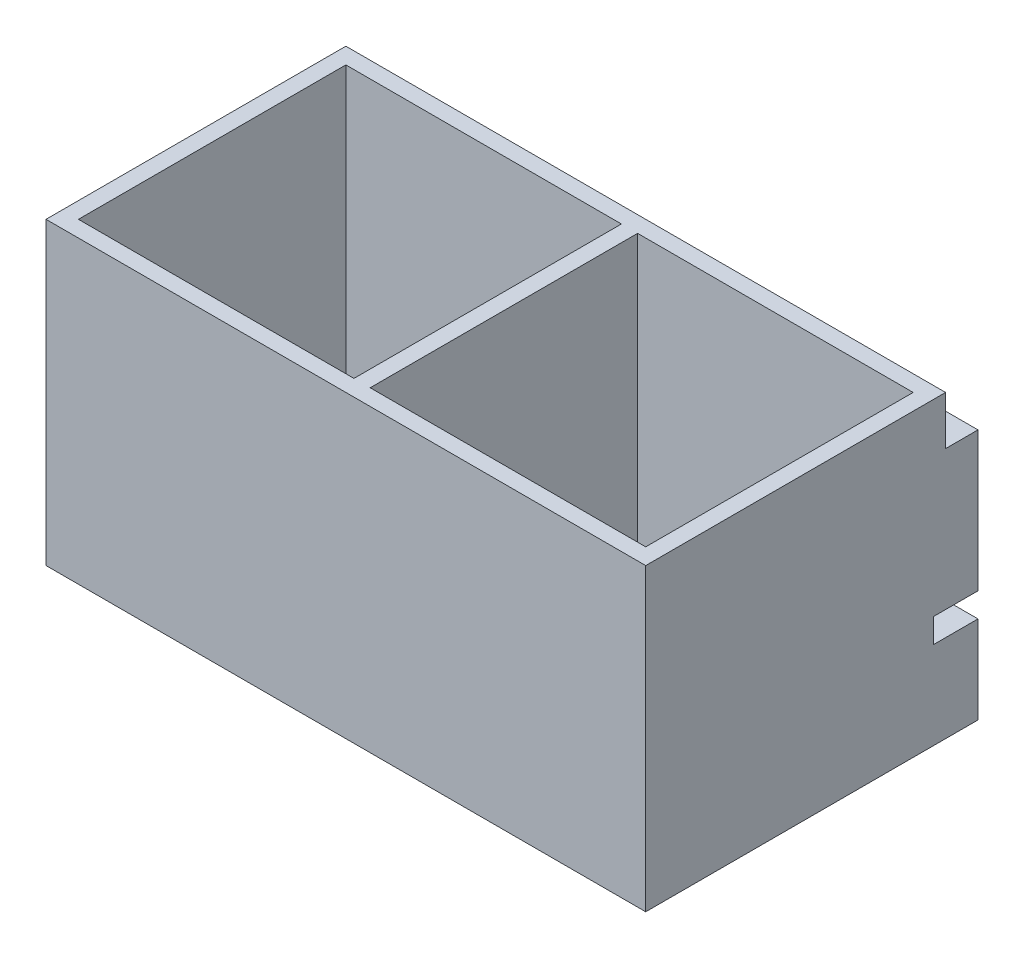
SolidWorks part; units mm, degrees
ref_plane "Front Plane" through (0, 0, 0) normal (0, 0, 1) x (1, 0, 0)
ref_plane "Top Plane" through (0, 0, 0) normal (0, 1, 0) x (1, 0, 0)
ref_plane "Right Plane" through (0, 0, 0) normal (1, 0, 0) x (0, 0, -1)
sketch "Sketch1" plane through (0, 0, 0) normal (0, 1, 0) x (1, 0, 0)
  line L1 (-70.6, 1.0159) -> (3.4, 1.0159)
  line L2 (-70.6, 1.0159) -> (-70.6, -35.9841)
  line L3 (-70.6, -35.9841) -> (3.4, -35.9841)
  line L4 (3.4, 1.0159) -> (3.4, -35.9841)
  dimension "D1" = 74
  dimension "D2" = 37
extrude "Boss-Extrude1" add sketch "Sketch1" along normal blind 37
sketch "Sketch3" plane through (0, 37, 0) normal (0, 1, 0) x (1, 0, 0)
  line L0 (-70.6, 1.0159) -> (-70.6, -35.9841) construction
  line L1 (-68.6, -0.9841) -> (-34.6, -0.9841)
  line L2 (-68.6, -0.9841) -> (-68.6, -33.9841)
  line L3 (-68.6, -33.9841) -> (-34.6, -33.9841)
  line L4 (-34.6, -0.9841) -> (-34.6, -33.9841)
  line L5 (-32.6, -0.9841) -> (1.4, -0.9841)
  line L6 (-32.6, -0.9841) -> (-32.6, -33.9841)
  line L7 (-32.6, -33.9841) -> (1.4, -33.9841)
  line L8 (1.4, -0.9841) -> (1.4, -33.9841)
  line L9 (3.4, 1.0159) -> (-70.6, 1.0159) construction
  line L10 (-70.6, -35.9841) -> (3.4, -35.9841) construction
  line L11 (3.4, -35.9841) -> (3.4, 1.0159) construction
  dimension "D1" = 2
  dimension "D2" = 2
  dimension "D3" = 2
  dimension "D4" = 2
  dimension "D5" = 2
  dimension "D6" = 2
  dimension "D7" = 34
  dimension "D8" = 34
extrude "Cut-Extrude1" cut sketch "Sketch3" against normal blind 35
sketch "Sketch5" plane through (0, 2, 0) normal (0, 1, 0) x (1, 0, 0)
  line L0 (-70.6, -35.9841) -> (3.4, -35.9841) construction
  line L1 (3.4, -35.9841) -> (3.4, 1.0159) construction
  line L2 (-70.6, 1.0159) -> (-70.6, -35.9841) construction
  circle A0 centre (-15.1, -17.4841) radius 13
  circle A1 centre (-52.1, -17.4841) radius 13
  dimension "D1" = 26
  dimension "D2" = 26
  dimension "D3" = 18.5
  dimension "D4" = 18.5
  dimension "D5" = 18.5
  dimension "D6" = 18.5
extrude "Cut-Extrude2" cut sketch "Sketch5" against normal blind 3.5
sketch "Sketch6" plane through (0, 0, -1.0159) normal (0, 0, -1) x (-1, 0, 0)
  line L0 (-3.4, 37) -> (-3.4, 0) construction
  line L1 (-3.4, 31) -> (70.6, 31)
  line L2 (-3.4, 31) -> (-3.4, 0)
  line L3 (-3.4, 0) -> (70.6, 0)
  line L4 (70.6, 31) -> (70.6, 0)
  dimension "D1" = 31
extrude "Boss-Extrude2" add sketch "Sketch6" along normal blind 4
sketch "Sketch8" plane through (0, 0, -5.0159) normal (0, 0, -1) x (-1, 0, 0)
  line L0 (70.6, 31) -> (-3.4, 31) construction
  line L1 (4.6, 29) -> (28.6, 29)
  line L2 (4.6, 29) -> (4.6, 13.8)
  line L3 (4.6, 0) -> (28.6, 0)
  line L4 (28.6, 29) -> (28.6, 13.8)
  line L5 (38.6, 29) -> (62.6, 29)
  line L6 (38.6, 29) -> (38.6, 13.8)
  line L7 (38.6, 0) -> (62.6, 0)
  line L8 (62.6, 29) -> (62.6, 13.8)
  line L9 (70.6, 31) -> (-3.4, 31) construction
  line L10 (-3.4, 0) -> (70.6, 0) construction
  line L11 (34.6, 2) -> (34.6, 37) construction
  line L12 (-3.4, 31) -> (-3.4, 0) construction
  line L13 (-3.4, 13.8) -> (4.6, 13.8)
  line L14 (-3.4, 13.8) -> (-3.4, 10.8)
  line L15 (-3.4, 10.8) -> (4.6, 10.8)
  line L16 (70.6, 13.8) -> (70.6, 10.8)
  line L17 (70.6, 0) -> (70.6, 31) construction
  line L18 (28.6, 13.8) -> (38.6, 13.8)
  line L19 (28.6, 10.8) -> (38.6, 10.8)
  line L20 (62.6, 13.8) -> (70.6, 13.8)
  line L21 (62.6, 10.8) -> (70.6, 10.8)
  line L22 (38.6, 10.8) -> (38.6, 0)
  line L23 (28.6, 10.8) -> (28.6, 0)
  line L24 (62.6, 10.8) -> (62.6, 0)
  line L25 (4.6, 10.8) -> (4.6, 0)
  dimension "D1" = 24
  dimension "D2" = 24
  dimension "D3" = 2
  dimension "D4" = 2
  dimension "D5" = 10
  dimension "D6" = 0
  dimension "D7" = 0
  dimension "D8" = 4
  dimension "D9" = 0
  dimension "D10" = 0
  dimension "D11" = 3
  dimension "D12" = 18.2
extrude "Cut-Extrude3" cut sketch "Sketch8" against normal blind 5.5
